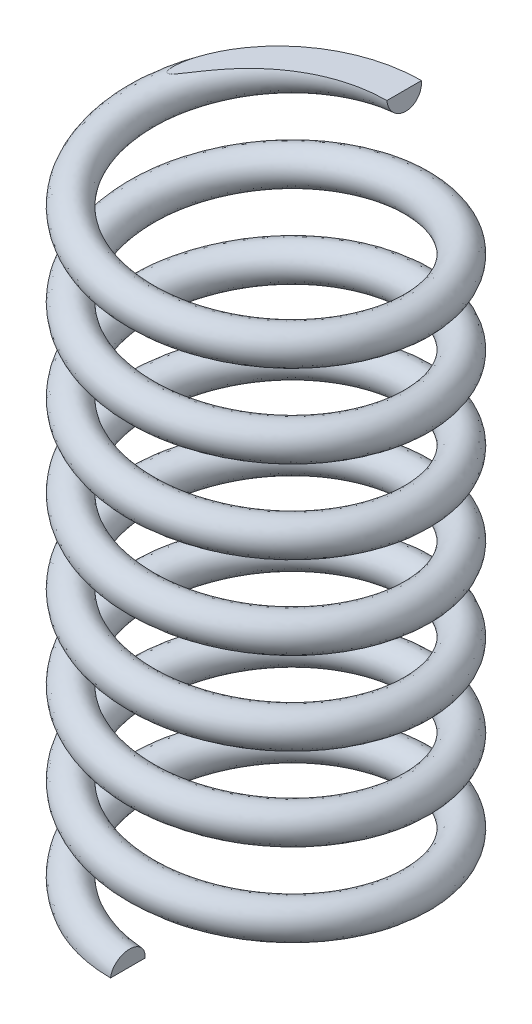
SolidWorks part; units mm, degrees
ref_plane "Front Plane" through (0, 0, 0) normal (0, 0, 1) x (1, 0, 0)
ref_plane "Top Plane" through (0, 0, 0) normal (0, 1, 0) x (1, 0, 0)
ref_plane "Right Plane" through (0, 0, 0) normal (1, 0, 0) x (0, 0, -1)
sketch "Sketch1" plane through (0, 0, 0) normal (0, 1, 0) x (1, 0, 0)
  circle A0 centre (0, 0) radius 20
  dimension "D1" = 40
curve "Helix/Spiral1" pitch 12 height 90 turns 7.5
sweep "Coil Wire Sweep" add path "Helix/Spiral1" circular profile diameter 5 parameters "D3"=5
sketch "Sketch8" plane through (0, 0, 0) normal (0, 1, 0) x (1, 0, 0)
  circle A0 centre (0, 0) radius 30
  dimension "D1" = 60
extrude "Bottom Ground Seat Cut" cut sketch "Sketch8" against normal through all
ref_plane "Top Seat Reference Plane" through (0, 90, 0) normal (0, 1, 0) x (1, 0, 0)
sketch "Sketch9" plane through (0, 90, 0) normal (0, 1, 0) x (1, 0, 0)
  circle A0 centre (0, 0) radius 30
  dimension "D1" = 60
extrude "Top Ground Seat Cut" cut sketch "Sketch9" along normal through all
